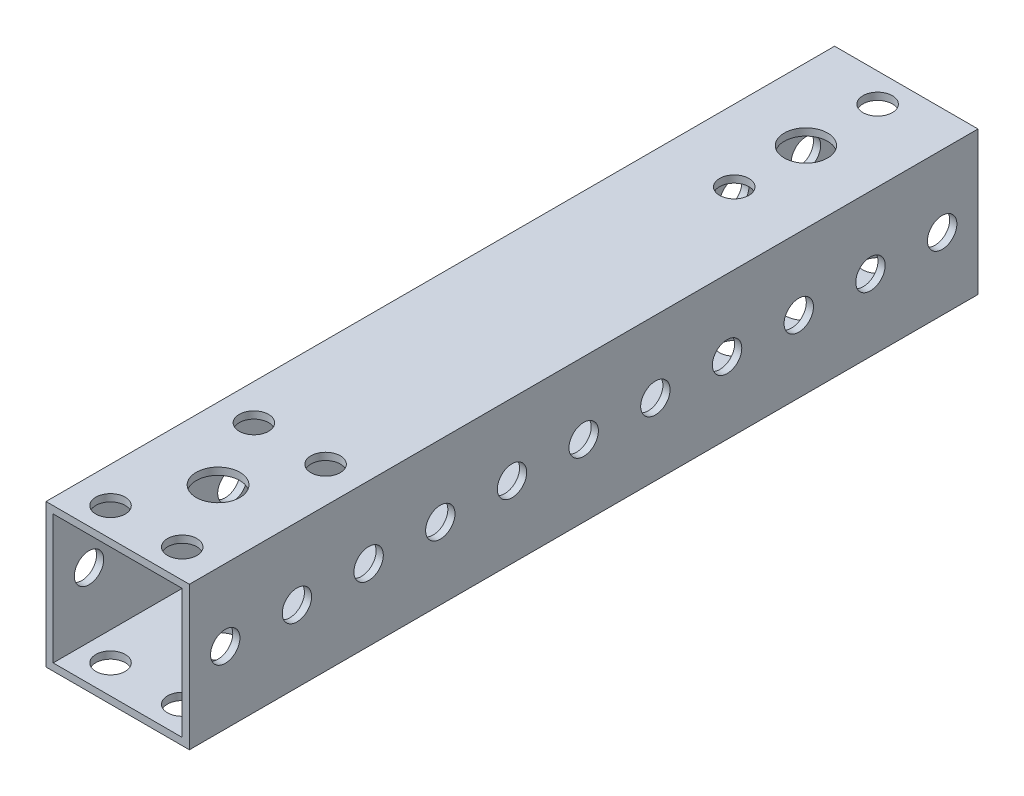
SolidWorks part; units mm, degrees
material "1060 合金"
ref_plane "前视基准面" through (0, 0, 0) normal (0, 0, 1) x (1, 0, 0)
ref_plane "上视基准面" through (0, 0, 0) normal (0, 1, 0) x (1, 0, 0)
ref_plane "右视基准面" through (0, 0, 0) normal (1, 0, 0) x (0, 0, -1)
other "Configuration Table"
sketch "草图1" plane through (0, 0, 0) normal (0, 0, 1) x (1, 0, 0)
  line L0 (-10, -10) -> (-10, 10)
  line L1 (-9, -9) -> (9, -9)
  line L2 (-9, -9) -> (-9, 9)
  line L3 (-9, 9) -> (9, 9)
  line L4 (9, -9) -> (9, 9)
  line L5 (-9, -9) -> (9, 9) construction
  line L6 (-9, 9) -> (9, -9) construction
  line L7 (-10, 10) -> (10, 10)
  line L8 (10, -10) -> (10, 10)
  line L9 (-10, -10) -> (10, -10)
  point P0 (0, 0)
  dimension "D1" = 1
  dimension "D2" = 20
extrude "凸台-拉伸1" add sketch "草图1" along normal mid plane 110
sketch "草图3" plane through (0, 10, 0) normal (0, 1, 0) x (1, 0, 0)
  line L0 (0, 0) -> (0, -50000) construction
  line L1 (10, -55) -> (-10, -55) construction
  line L2 (-5, -51) -> (5, -51) construction
  line L3 (-5, -51) -> (-5, -31) construction
  line L4 (-5, -31) -> (5, -31) construction
  line L5 (5, -51) -> (5, -31) construction
  line L6 (-5, -51) -> (5, -31) construction
  line L7 (-5, -31) -> (5, -51) construction
  line L8 (0, 0) -> (50000, 0) construction
  circle A0 centre (-5, -31) radius 2.05
  circle A1 centre (5, -31) radius 2.05
  circle A2 centre (5, -51) radius 2.05
  circle A3 centre (-5, -51) radius 2.05
  circle A4 centre (0, -41) radius 3.05
  point P3 (0, -41)
  dimension "D2" = 4.1
  dimension "D3" = 6.1
  dimension "D1" = 4
  dimension "D4" = 10
  dimension "D5" = 20
extrude "切除-拉伸1" cut sketch "草图3" against normal blind 20
sketch "草图4" plane through (0, -10, 0) normal (0, -1, 0) x (1, 0, 0)
  line L0 (0, -55) -> (0, -51) construction
  line L1 (-10, -55) -> (10, -55) construction
  line L2 (0, -51) -> (0, -31) construction
  circle A0 centre (0, -51) radius 2.05
  circle A1 centre (0, -31) radius 2.05
  circle A4 centre (0, -41) radius 3.025
  dimension "D3" = 4.1
  dimension "D4" = 6.05
  dimension "D1" = 20
  dimension "D2" = 4
extrude "切除-拉伸2" cut sketch "草图4" against normal through all
sketch "草图5" plane through (10, 0, 0) normal (1, 0, 0) x (0, 0, -1)
  line L1 (-55, 0) -> (55, 0) construction
  line L2 (-55, -10) -> (-55, 10) construction
  line L3 (55, -10) -> (55, 10) construction
  circle A0 centre (-50, 0) radius 2.05
  circle A1 centre (-40, 0) radius 2.05
  circle A2 centre (-30, 0) radius 2.05
  circle A3 centre (-20, 0) radius 2.05
  circle A4 centre (-10, 0) radius 2.05
  circle A5 centre (0, 0) radius 2.05
  circle A6 centre (10, 0) radius 2.05
  circle A7 centre (20, 0) radius 2.05
  circle A8 centre (30, 0) radius 2.05
  circle A9 centre (40, 0) radius 2.05
  circle A10 centre (50, 0) radius 2.05
  dimension "D1" = 4.1
  dimension "D3" = 5
  dimension "D4" = 5
  dimension "D2" = 11
extrude "切除-拉伸3" cut sketch "草图5" against normal blind 30
